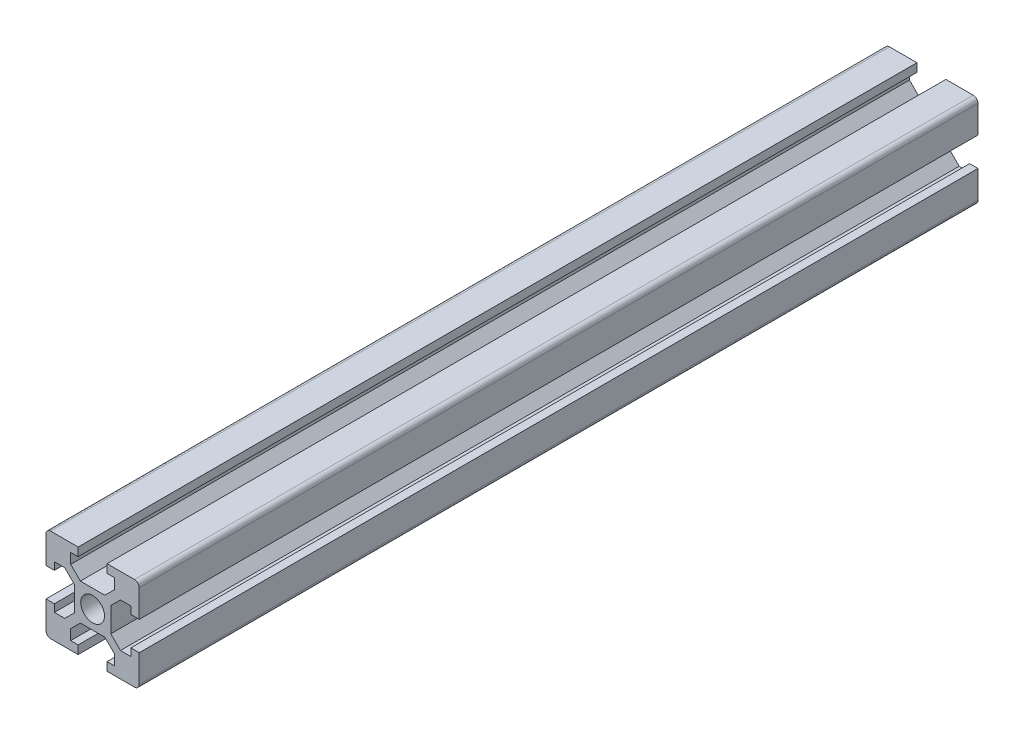
SolidWorks part; units mm, degrees
ref_plane "前视基准面" through (0, 0, 0) normal (0, 0, 1) x (1, 0, 0)
ref_plane "上视基准面" through (0, 0, 0) normal (0, 1, 0) x (1, 0, 0)
ref_plane "右视基准面" through (0, 0, 0) normal (1, 0, 0) x (0, 0, -1)
sketch "草图1" plane through (0, 0, 0) normal (0, 0, 1) x (1, 0, 0)
  line L0 (4.6219, 1.9053) -> (6.6947, 3.9781)
  line L1 (-8.0053, 8.0053) -> (-1.1053, 8.0053)
  line L2 (-8.0053, 8.0053) -> (-8.0053, 1.1053)
  line L3 (-8.0053, -11.9947) -> (-1.1053, -11.9947)
  line L4 (11.9947, 8.0053) -> (11.9947, 1.1053)
  line L5 (-8.0053, 8.0053) -> (11.9947, -11.9947) construction
  line L6 (5.8947, 0.6325) -> (7.9675, 2.7053)
  line L7 (-0.6325, -5.8947) -> (4.6219, -5.8947)
  line L8 (-1.9053, -4.6219) -> (-1.9053, 0.6325)
  line L9 (-0.6325, 1.9053) -> (4.6219, 1.9053)
  line L10 (5.8947, -4.6219) -> (5.8947, 0.6325)
  line L11 (-2.53, -6.5195) -> (5.8947, 1.9053) construction
  line L12 (-2.53, 2.53) -> (5.8947, -5.8947) construction
  line L13 (7.9675, 2.7053) -> (10.1947, 2.7053)
  line L14 (6.6947, 3.9781) -> (6.6947, 6.2053)
  line L15 (6.6947, 6.2053) -> (5.0947, 6.2053)
  line L16 (5.0947, 6.2053) -> (5.0947, 8.0053)
  line L17 (10.1947, 2.7053) -> (10.1947, 1.1053)
  line L18 (10.1947, 1.1053) -> (11.9947, 1.1053)
  line L19 (1.9947, -1.9947) -> (1.9947, 14.4959) construction
  line L20 (-6.2053, 1.1053) -> (-8.0053, 1.1053)
  line L21 (-6.2053, 2.7053) -> (-6.2053, 1.1053)
  line L22 (-1.9053, 0.6325) -> (-3.9781, 2.7053)
  line L23 (-3.9781, 2.7053) -> (-6.2053, 2.7053)
  line L24 (-2.7053, 3.9781) -> (-2.7053, 6.2053)
  line L25 (-0.6325, 1.9053) -> (-2.7053, 3.9781)
  line L26 (-2.7053, 6.2053) -> (-1.1053, 6.2053)
  line L27 (-1.1053, 6.2053) -> (-1.1053, 8.0053)
  line L28 (1.9947, -1.9947) -> (-12.4459, -1.9947) construction
  line L29 (-1.9053, -4.6219) -> (-3.9781, -6.6947)
  line L30 (-0.6325, -5.8947) -> (-2.7053, -7.9675)
  line L31 (4.6219, -5.8947) -> (6.6947, -7.9675)
  line L32 (5.8947, -4.6219) -> (7.9675, -6.6947)
  line L33 (-6.2053, -5.0947) -> (-8.0053, -5.0947)
  line L34 (10.1947, -5.0947) -> (11.9947, -5.0947)
  line L35 (-1.1053, -10.1947) -> (-1.1053, -11.9947)
  line L36 (5.0947, -10.1947) -> (5.0947, -11.9947)
  line L37 (-2.7053, -10.1947) -> (-1.1053, -10.1947)
  line L38 (-2.7053, -7.9675) -> (-2.7053, -10.1947)
  line L39 (-3.9781, -6.6947) -> (-6.2053, -6.6947)
  line L40 (-6.2053, -6.6947) -> (-6.2053, -5.0947)
  line L41 (10.1947, -6.6947) -> (10.1947, -5.0947)
  line L42 (6.6947, -10.1947) -> (5.0947, -10.1947)
  line L43 (6.6947, -7.9675) -> (6.6947, -10.1947)
  line L44 (7.9675, -6.6947) -> (10.1947, -6.6947)
  line L45 (11.9947, -5.0947) -> (11.9947, -11.9947)
  line L46 (5.0947, 8.0053) -> (11.9947, 8.0053)
  line L47 (-8.0053, -5.0947) -> (-8.0053, -11.9947)
  line L48 (5.0947, -11.9947) -> (11.9947, -11.9947)
  circle A0 centre (1.9947, -1.9947) radius 2.55
  point P0 (0, 0)
  point P6 (1.9947, -1.9947)
  dimension "D4" = 5.1
  dimension "D1" = 20
  dimension "D2" = 20
  dimension "D3" = 7.8
  dimension "D5" = 6.2
  dimension "D6" = 9.4
  dimension "D7" = 0.9
  dimension "D8" = 1.8
extrude "凸台-拉伸1" add sketch "草图1" along normal blind 180
fillet "圆角1" radius 1 4 edges at (11.9947, -11.9947, 90) (-8.0053, -11.9947, 90) (11.9947, 8.0053, 90) (-8.0053, 8.0053, 90)
